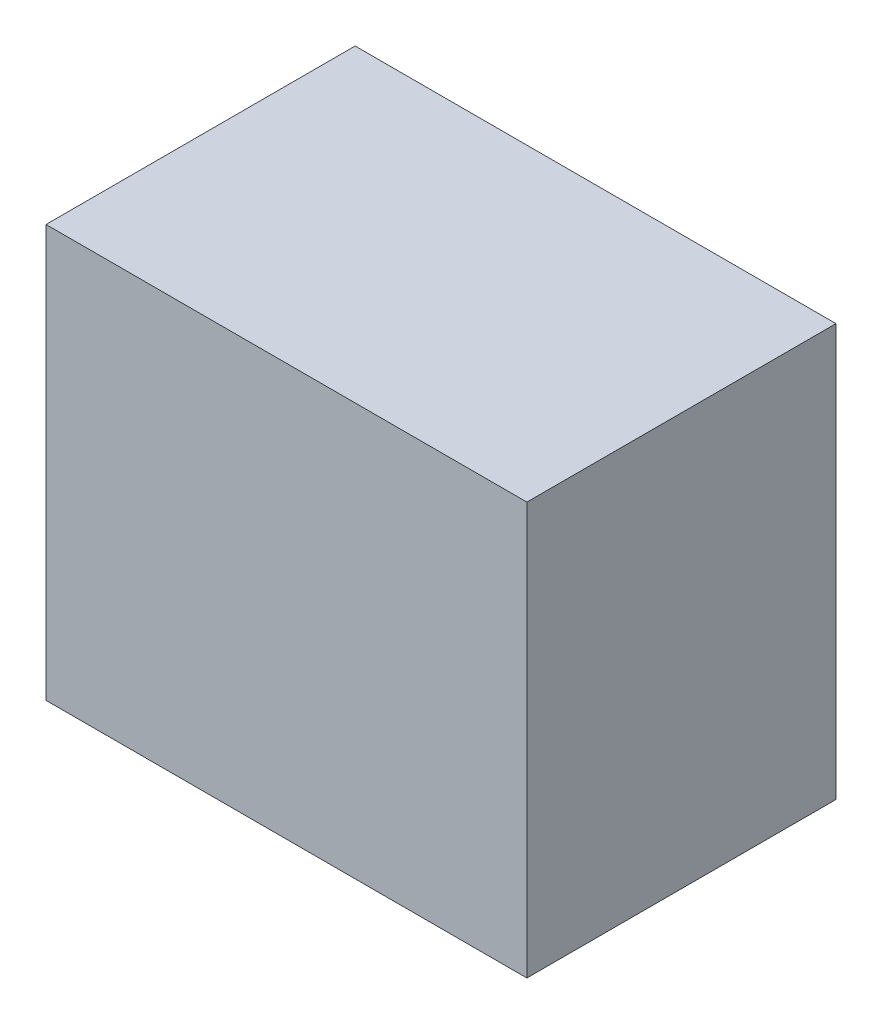
SolidWorks part; units mm, degrees
material "Q235A "
ref_plane "前视基准面" through (0, 0, 0) normal (0, 0, 1) x (1, 0, 0)
ref_plane "上视基准面" through (0, 0, 0) normal (0, 1, 0) x (1, 0, 0)
ref_plane "右视基准面" through (0, 0, 0) normal (1, 0, 0) x (0, 0, -1)
sketch "草图1" plane through (0, 0, 0) normal (0, 1, 0) x (1, 0, 0)
  line L0 (175.8098, 0) -> (0, 0) construction
  line L1 (-350, 225) -> (350, 225)
  line L2 (-350, 225) -> (-350, -225)
  line L3 (-350, -225) -> (350, -225)
  line L4 (350, 225) -> (350, -225)
  line L5 (0, 0) -> (0, 129.6513) construction
  dimension "D1" = 700
  dimension "D2" = 450
extrude "凸台-拉伸1" add sketch "草图1" along normal blind 600
sketch "草图2" plane through (-350, 0, 0) normal (-1, 0, 0) x (0, 0, 1)
  line L1 (13.361, 148.8097) -> (139.939, 148.8097)
  line L2 (13.361, 148.8097) -> (13.361, 54.5794)
  line L3 (13.361, 54.5794) -> (139.939, 54.5794)
  line L4 (139.939, 148.8097) -> (139.939, 54.5794)
extrude "凸台-拉伸2" add sketch "草图2" along normal blind 80
sketch "草图3" plane through (0, 0, -225) normal (0, 0, -1) x (-1, 0, 0)
  line L0 (350, 600) -> (350, 0) construction
  line L1 (-350, 0) -> (350, 0) construction
  circle A0 centre (160, 190) radius 100
  dimension "D1" = 200
  dimension "D2" = 190
  dimension "D3" = 190
extrude "切除-拉伸1" cut sketch "草图3" against normal blind 2
sketch "草图4" plane through (0, 0, -225) normal (0, 0, -1) x (-1, 0, 0)
  line L0 (-350, 600) -> (-350, 0) construction
  line L1 (-290, 560) -> (-90, 560)
  line L2 (-290, 560) -> (-290, 475)
  line L3 (-290, 475) -> (-90, 475)
  line L4 (-90, 560) -> (-90, 475)
  line L5 (-350, 600) -> (350, 600) construction
  dimension "D1" = 60
  dimension "D2" = 40
  dimension "D3" = 85
  dimension "D4" = 200
extrude "凸台-拉伸3" add sketch "草图4" along normal blind 2
sketch "草图5" plane through (0, 0, -227) normal (0, 0, -1) x (-1, 0, 0)
  line L0 (-90, 517.5) -> (-130, 517.5) construction
  line L1 (-90, 475) -> (-90, 560) construction
  circle A0 centre (-130, 517.5) radius 15
  dimension "D1" = 40
  dimension "D2" = 30
extrude "凸台-拉伸4" add sketch "草图5" along normal blind 30
sketch "草图6" plane through (0, 0, -225) normal (0, 0, -1) x (-1, 0, 0)
  line L0 (-350, 600) -> (-350, 0) construction
  line L1 (-290, 355) -> (-230, 355)
  line L2 (-290, 355) -> (-290, 235)
  line L3 (-290, 235) -> (-230, 235)
  line L4 (-230, 355) -> (-230, 235)
  line L5 (-290, 475) -> (-90, 475) construction
  dimension "D1" = 60
  dimension "D2" = 60
  dimension "D3" = 120
  dimension "D4" = 120
extrude "凸台-拉伸5" add sketch "草图6" along normal blind 5
sketch "草图7" plane through (0, 0, -225) normal (0, 0, -1) x (-1, 0, 0)
  line L0 (-135, 129.282) -> (-175, 60)
  line L1 (-305, 130) -> (-220, 130)
  line L2 (-305, 130) -> (-305, 60)
  line L3 (-305, 60) -> (-220, 60)
  line L4 (-220, 130) -> (-220, 60)
  line L5 (-175, 60) -> (-95, 60)
  line L6 (-95, 60) -> (-135, 129.282)
  line L7 (-350, 600) -> (-350, 0) construction
  line L8 (-350, 0) -> (350, 0) construction
  dimension "D1" = 45
  dimension "D2" = 85
  dimension "D3" = 70
  dimension "D4" = 60
  dimension "D5" = 80
  dimension "D6" = 45
extrude "凸台-拉伸6" add sketch "草图7" along normal blind 1
sketch "草图8" plane through (0, 0, -225) normal (0, 0, -1) x (-1, 0, 0)
  line L0 (-90, 560) -> (-290, 560) construction
  line L1 (10, 560) -> (13, 560)
  line L2 (10, 560) -> (10, 475)
  line L3 (10, 475) -> (13, 475)
  line L4 (13, 560) -> (13, 475)
  line L5 (-290, 475) -> (-90, 475) construction
  line L6 (-90, 475) -> (-90, 560) construction
  dimension "D1" = 3
  dimension "D2" = 100
extrude "切除-拉伸2" cut sketch "草图8" against normal blind 2
pattern_linear "阵列(线性)1" count 38 spacing 8 along (-1, 0, 0) of "切除-拉伸2"
